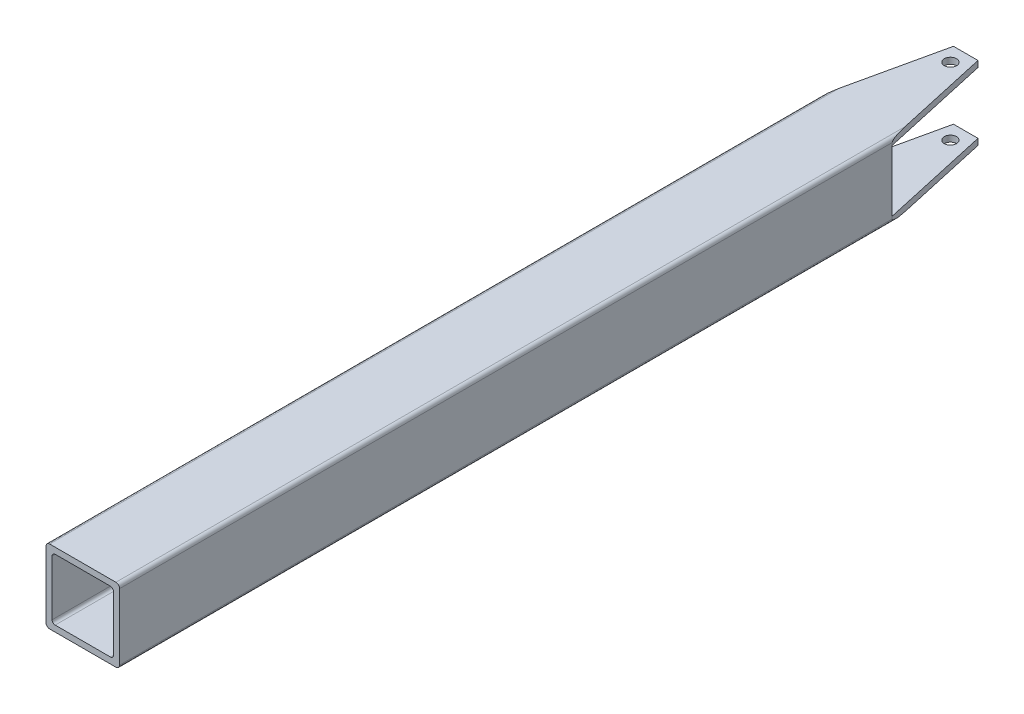
SolidWorks part; units mm, degrees
ref_plane "Front" through (0, 0, 0) normal (0, 0, 1) x (1, 0, 0)
ref_plane "Top" through (0, 0, 0) normal (0, 1, 0) x (1, 0, 0)
ref_plane "Right" through (0, 0, 0) normal (1, 0, 0) x (0, 0, -1)
sketch "Sketch1" plane through (0, 0, 0) normal (0, 0, 1) x (1, 0, 0)
  line L0 (-31.75, 0) -> (-38.1, 0) construction
  line L1 (34.29, -38.1) -> (-34.29, -38.1)
  line L2 (38.1, -34.29) -> (38.1, 34.29)
  line L3 (34.29, 38.1) -> (-34.29, 38.1)
  line L4 (-38.1, -34.29) -> (-38.1, 34.29)
  line L5 (38.1, -38.1) -> (-38.1, 38.1) construction
  line L6 (38.1, 38.1) -> (-38.1, -38.1) construction
  line L7 (28.575, 31.75) -> (-28.575, 31.75)
  line L8 (31.75, 28.575) -> (31.75, -28.575)
  line L9 (28.575, -31.75) -> (-28.575, -31.75)
  line L10 (-31.75, 28.575) -> (-31.75, -28.575)
  line L11 (31.75, 31.75) -> (-31.75, -31.75) construction
  line L12 (31.75, -31.75) -> (-31.75, 31.75) construction
  line L13 (0, -31.75) -> (0, -38.1) construction
  line L14 (31.75, -28.575) -> (31.75, -38.1) construction
  line L16 (31.75, -38.1) -> (38.1, -38.1) construction
  arc A0 (-28.575, -31.75) -> (-31.75, -28.575) centre (-28.575, -28.575) cw
  arc A1 (31.75, -28.575) -> (28.575, -31.75) centre (28.575, -28.575) cw
  arc A2 (28.575, 31.75) -> (31.75, 28.575) centre (28.575, 28.575) cw
  arc A3 (-28.575, 31.75) -> (-31.75, 28.575) centre (-28.575, 28.575) ccw
  arc A4 (34.29, -38.1) -> (38.1, -34.29) centre (34.29, -34.29) ccw
  arc A5 (38.1, 34.29) -> (34.29, 38.1) centre (34.29, 34.29) ccw
  arc A6 (-34.29, 38.1) -> (-38.1, 34.29) centre (-34.29, 34.29) ccw
  arc A7 (-34.29, -38.1) -> (-38.1, -34.29) centre (-34.29, -34.29) cw
  point P0 (0, 0)
  point P6 (0, 0)
  dimension "D2" = 3.175
  dimension "D3" = 3.81
sketch "Sketch2" plane through (0, 0, 0) normal (1, 0, 0) x (0, 0, -1)
  line L0 (-457.2, 0) -> (457.2, 0) construction
  dimension "Length" = 914.4
ref_plane "Plane1" through (38.1, 0, 0) normal (1, 0, 0) x (0, 0, -1)
sketch "Sketch5" plane through (38.1, 0, 0) normal (1, 0, 0) x (0, 0, -1)
  line L0 (-457.2, 38.1) -> (-457.2, -38.1) construction
  line L1 (457.2, 38.1) -> (457.2, -38.1) construction
sketch "Sketch4" plane through (0, 0, 0) normal (0, 0, 1) x (1, 0, 0)
  line L0 (38.1, -34.29) -> (38.1, 34.29) construction
  line L1 (34.29, 38.1) -> (-34.29, 38.1) construction
  line L2 (-38.1, -34.29) -> (-38.1, 34.29) construction
  line L3 (34.29, -38.1) -> (-34.29, -38.1) construction
  line L4 (31.75, 28.575) -> (31.75, -28.575) construction
  line L5 (28.575, -31.75) -> (-28.575, -31.75) construction
  line L6 (-31.75, 28.575) -> (-31.75, -28.575) construction
  line L7 (28.575, 31.75) -> (-28.575, 31.75) construction
  line L8 (38.1, -34.29) -> (38.1, 34.29)
  line L9 (34.29, 38.1) -> (-34.29, 38.1)
  line L10 (-38.1, -34.29) -> (-38.1, 34.29)
  line L11 (34.29, -38.1) -> (-34.29, -38.1)
  line L12 (31.75, 28.575) -> (31.75, -28.575)
  line L13 (28.575, -31.75) -> (-28.575, -31.75)
  line L14 (-31.75, 28.575) -> (-31.75, -28.575)
  line L15 (28.575, 31.75) -> (-28.575, 31.75)
  arc A0 (38.1, 34.29) -> (34.29, 38.1) centre (34.29, 34.29) ccw construction
  arc A1 (-34.29, 38.1) -> (-38.1, 34.29) centre (-34.29, 34.29) ccw construction
  arc A2 (-38.1, -34.29) -> (-34.29, -38.1) centre (-34.29, -34.29) ccw construction
  arc A3 (34.29, -38.1) -> (38.1, -34.29) centre (34.29, -34.29) ccw construction
  arc A4 (28.575, -31.75) -> (31.75, -28.575) centre (28.575, -28.575) ccw construction
  arc A5 (-31.75, -28.575) -> (-28.575, -31.75) centre (-28.575, -28.575) ccw construction
  arc A6 (-28.575, 31.75) -> (-31.75, 28.575) centre (-28.575, 28.575) ccw construction
  arc A7 (31.75, 28.575) -> (28.575, 31.75) centre (28.575, 28.575) ccw construction
  arc A8 (38.1, 34.29) -> (34.29, 38.1) centre (34.29, 34.29) ccw
  arc A9 (-34.29, 38.1) -> (-38.1, 34.29) centre (-34.29, 34.29) ccw
  arc A10 (-38.1, -34.29) -> (-34.29, -38.1) centre (-34.29, -34.29) ccw
  arc A11 (34.29, -38.1) -> (38.1, -34.29) centre (34.29, -34.29) ccw
  arc A12 (28.575, -31.75) -> (31.75, -28.575) centre (28.575, -28.575) ccw
  arc A13 (-31.75, -28.575) -> (-28.575, -31.75) centre (-28.575, -28.575) ccw
  arc A14 (-28.575, 31.75) -> (-31.75, 28.575) centre (-28.575, 28.575) ccw
  arc A15 (31.75, 28.575) -> (28.575, 31.75) centre (28.575, 28.575) ccw
extrude "Boss-Extrude1" add sketch "Sketch4" along normal up to vertex (457.2 mm away) and the other way up to vertex (457.2 mm away) up to point (0, 0, 457.2) other way up to point (0, 0, -457.2)
sketch "Sketch6" plane through (-38.1, 0, 0) normal (-1, 0, 0) x (0, 0, 1)
  line L0 (-457.2, -31.75) -> (-371.4675, -31.75) construction
  line L1 (-457.2, 31.75) -> (-342.9, 31.75)
  line L2 (-457.2, 31.75) -> (-457.2, -31.75)
  line L3 (-457.2, -31.75) -> (-342.9, -31.75)
  line L4 (-342.9, 31.75) -> (-342.9, -31.75)
  point P5 (-457.2, -31.75)
  dimension "D1" = 114.3
extrude "side cut" cut sketch "Sketch6" against normal through all
sketch "Sketch7" plane through (0, -38.1, 0) normal (0, -1, 0) x (1, 0, 0)
  line L0 (0, -457.2) -> (0, -341.7828) construction
  line L1 (-34.29, -457.2) -> (34.29, -457.2) construction
  line L2 (-38.1, -342.9) -> (-38.1, -457.2)
  line L3 (-38.1, -457.2) -> (-12.7, -457.2)
  line L4 (-12.7, -457.2) -> (-38.1, -342.9)
  line L5 (12.7, -457.2) -> (38.1, -342.9)
  line L6 (38.1, -457.2) -> (12.7, -457.2)
  line L7 (38.1, -342.9) -> (38.1, -457.2)
  dimension "D1" = 25.4
extrude "triangle cut" cut sketch "Sketch7" against normal through all
sketch "Sketch8" plane through (0, 38.1, 0) normal (0, 1, 0) x (1, 0, 0)
  line L0 (0, 457.2) -> (0, 353.4841) construction
  line L1 (12.7, 457.2) -> (-12.7, 457.2) construction
  circle A0 centre (0, 441.325) radius 6.35
  dimension "D1" = 12.7
  dimension "D2" = 15.875
extrude "Cut-Extrude4" cut sketch "Sketch8" against normal through all
sketch "Sketch9" plane through (38.1, 0, 0) normal (1, 0, 0) x (0, 0, -1)
  line L0 (434.975, 34.925) -> (447.675, 34.925) construction
  line L1 (434.975, 38.1) -> (434.975, 31.75) construction
  line L2 (447.675, 31.75) -> (447.675, 38.1) construction
  line L3 (434.975, -34.925) -> (447.675, -34.925) construction
  line L4 (434.975, -31.75) -> (434.975, -38.1) construction
  line L5 (447.675, -38.1) -> (447.675, -31.75) construction
  line L6 (441.325, -34.925) -> (441.325, 34.925) construction
  line L7 (441.325, 0) -> (-66.675, 0)
  point P18 (-66.675, 0)
  dimension "D1" = 508
equation "\"D3@Sketch1\"=\"Outside Width@Sketch1\"*.05"
equation "\"D2@Sketch1\"=\"D1@Sketch1\"*.05"
equation "\"mountingPointDistance\"= 20"
equation "\"D1@Sketch9\"=\"mountingPointDistance\""
